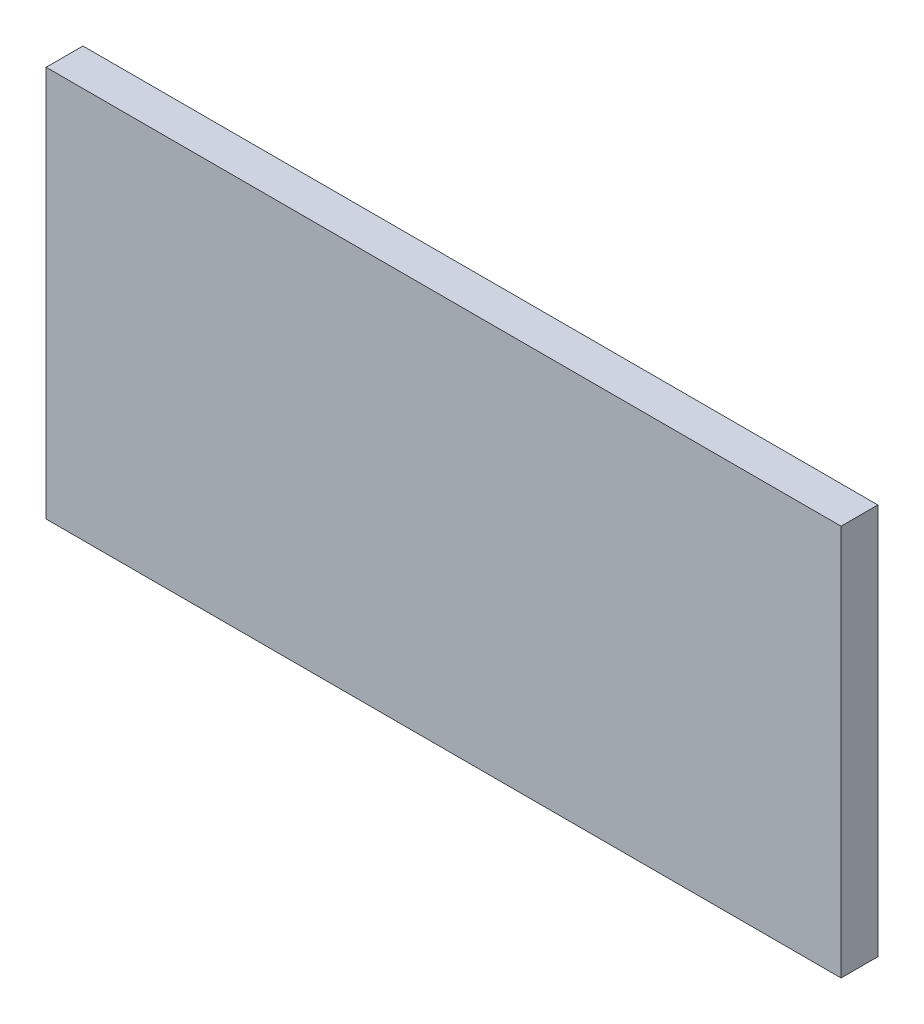
SolidWorks part; units mm, degrees
ref_plane "Front Plane" through (0, 0, 0) normal (0, 0, 1) x (1, 0, 0)
ref_plane "Top Plane" through (0, 0, 0) normal (0, 1, 0) x (1, 0, 0)
ref_plane "Right Plane" through (0, 0, 0) normal (1, 0, 0) x (0, 0, -1)
sketch "Sketch1" plane through (0, 0, 0) normal (0, 0, 1) x (1, 0, 0)
  line L1 (107.9884, -53.153) -> (-107.9884, -53.153)
  line L2 (107.9884, -53.153) -> (107.9884, 53.153)
  line L3 (107.9884, 53.153) -> (-107.9884, 53.153)
  line L4 (-107.9884, -53.153) -> (-107.9884, 53.153)
  line L5 (107.9884, -53.153) -> (-107.9884, 53.153) construction
  line L6 (107.9884, 53.153) -> (-107.9884, -53.153) construction
  point P0 (0, 0)
extrude "Boss-Extrude1" add sketch "Sketch1" along normal blind 10
ref_plane "Plane1" through (0, 0, 20) normal (0, 0, 1) x (1, 0, 0)
ref_plane "Plane2" through (0, 0, -10) normal (0, 0, -1) x (-1, 0, 0)
ref_plane "Plane3" through (0, 0, -20) normal (0, 0, -1) x (-1, 0, 0)
ref_plane "Plane4" through (0, 0, -30) normal (0, 0, -1) x (-1, 0, 0)
ref_plane "Plane5" through (0, 0, -40) normal (0, 0, -1) x (-1, 0, 0)
